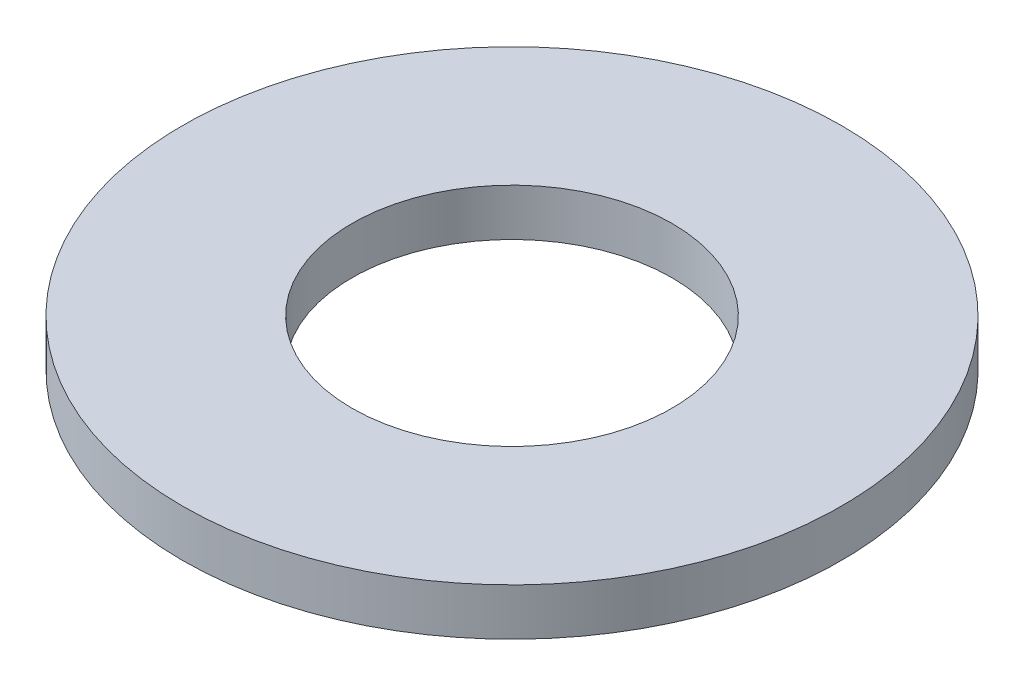
SolidWorks part; units mm, degrees
other "Frame Tie Washer"
ref_plane "Front Plane" through (0, 0, 0) normal (0, 0, 1) x (1, 0, 0)
ref_plane "Top Plane" through (0, 0, 0) normal (0, 1, 0) x (1, 0, 0)
ref_plane "Right Plane" through (0, 0, 0) normal (1, 0, 0) x (0, 0, -1)
sketch3d "Base Outline Sketch datum points"
  point P0 (0, -157.5, 0)
  point P1 (10, -157.5, 0)
  point P2 (0, -157.5, -10)
ref_plane "Base Outline Sketch plane" through (0, -157.5, 0) normal (0, 1, 0) x (1, 0, 0)
sketch "Base Outline Sketch" plane through (0, -157.5, 0) normal (0, 1, 0) x (1, 0, 0)
  circle A0 centre (-56.2917, -50) radius 3.5
  circle A1 centre (-56.2917, -50) radius 1.7
extrude "Base Outline" add sketch "Base Outline Sketch" along normal blind 0.5 separate body
